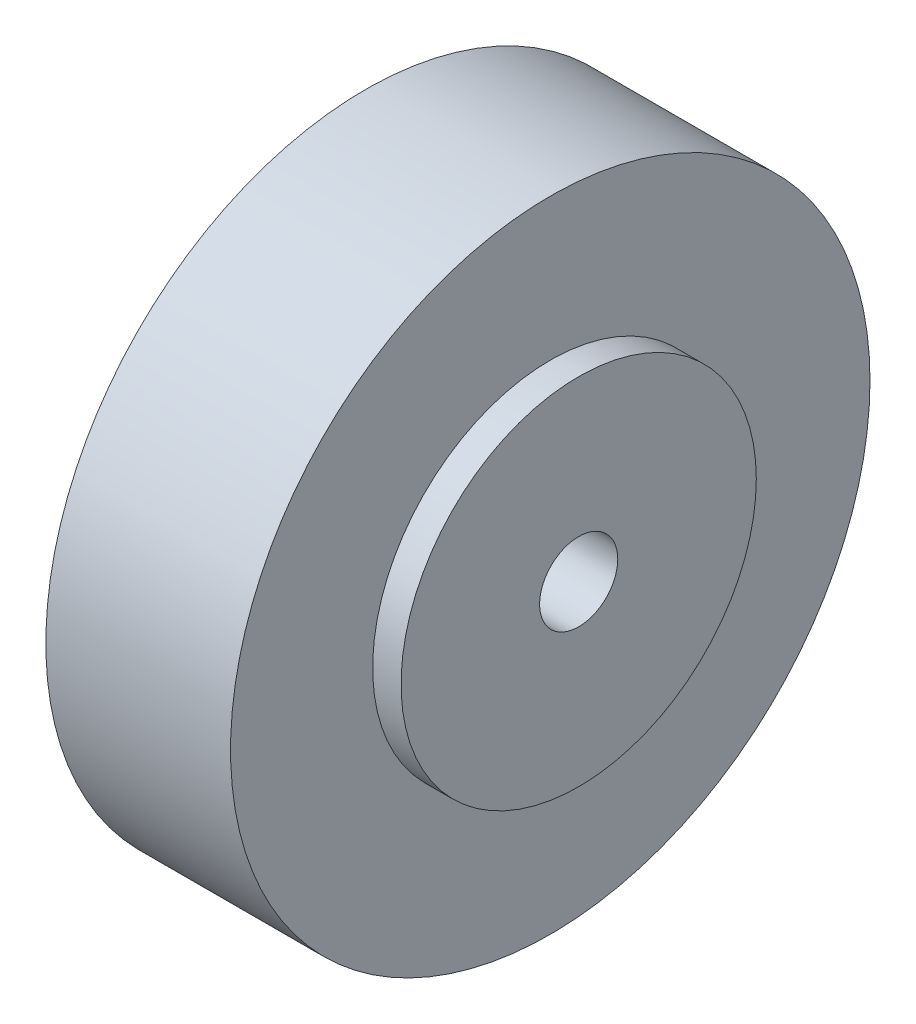
SolidWorks part; units mm, degrees
ref_plane "Front Plane" through (0, 0, 0) normal (0, 0, 1) x (1, 0, 0)
ref_plane "Top Plane" through (0, 0, 0) normal (0, 1, 0) x (1, 0, 0)
ref_plane "Right Plane" through (0, 0, 0) normal (1, 0, 0) x (0, 0, -1)
sketch "Sketch1" plane through (0, 0, 0) normal (1, 0, 0) x (0, 0, -1)
  circle A0 centre (0, 0) radius 22.5
  dimension "D1" = 45
extrude "Boss-Extrude1" add sketch "Sketch1" against normal blind 15
sketch "Sketch2" plane through (0, 0, 0) normal (1, 0, 0) x (0, 0, -1)
  circle A0 centre (0, 0) radius 2.75
  dimension "D1" = 5.5
extrude "Cut-Extrude1" cut sketch "Sketch2" against normal through all
sketch "Sketch5" plane through (-15, 0, 0) normal (-1, 0, 0) x (0, 0, 1)
  circle A0 centre (0, 0) radius 8.1
  dimension "D1" = 16.2
extrude "Cut-Extrude2" cut sketch "Sketch5" against normal blind 5.5
ref_plane "Plane2" through (-1.5, 0, 0) normal (1, 0, 0) x (0, 0, -1)
sketch "Sketch28" plane through (0, 0, 0) normal (1, 0, 0) x (0, 0, -1)
  circle A0 centre (0, 0) radius 12.5
  point P2 (0, 0)
  dimension "D1" = 25
extrude "Cut-Extrude-Thin1" cut sketch "Sketch28" against normal blind 2 thin
